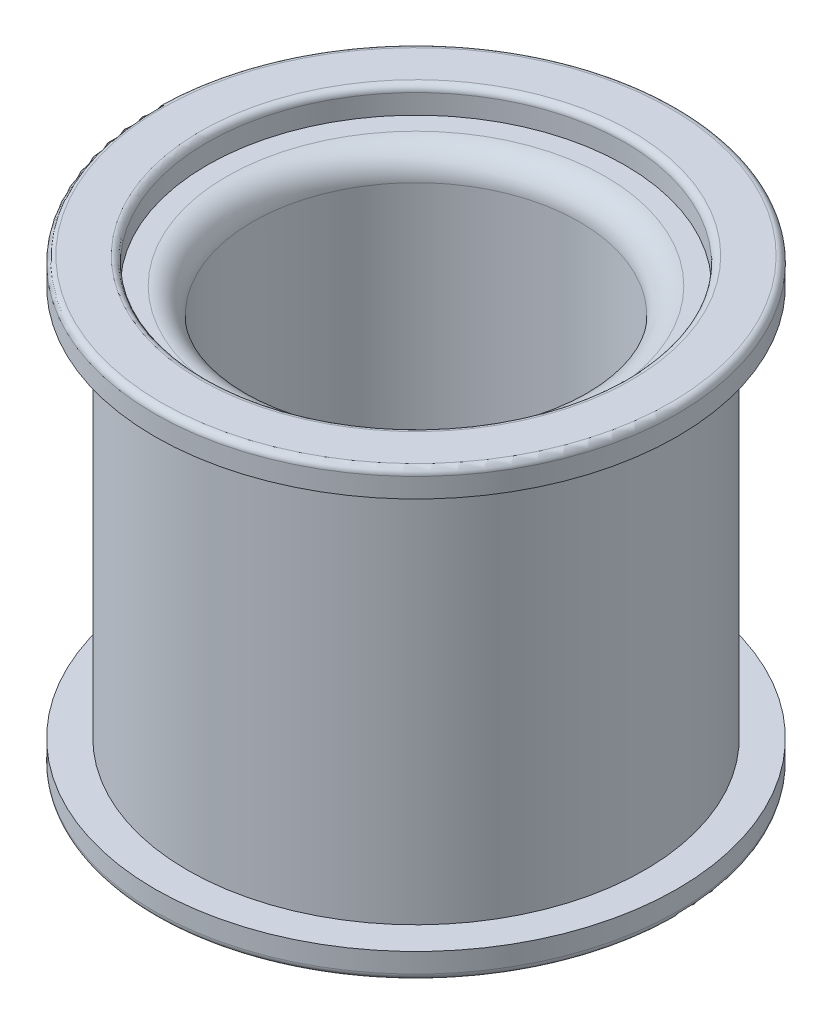
SolidWorks part; units mm, degrees
material "Guma"
ref_plane "Płaszczyzna przednia" through (0, 0, 0) normal (0, 0, 1) x (1, 0, 0)
ref_plane "Płaszczyzna górna" through (0, 0, 0) normal (0, 1, 0) x (1, 0, 0)
ref_plane "Płaszczyzna prawa" through (0, 0, 0) normal (1, 0, 0) x (0, 0, -1)
sketch "Szkic1" plane through (0, 0, 0) normal (0, 1, 0) x (1, 0, 0)
  circle A0 centre (0, 0) radius 17.5
  circle A1 centre (0, 0) radius 12.5
  dimension "D1" = 25
  dimension "D2" = 35
extrude "Dodanie-wyciągnięcie1" add sketch "Szkic1" along normal blind 15
sketch "Szkic2" plane through (0, 15, 0) normal (0, 1, 0) x (1, 0, 0)
  circle A0 centre (0, 0) radius 20
  circle A1 centre (0, 0) radius 16
  dimension "D1" = 40
  dimension "D2" = 32
extrude "Dodanie-wyciągnięcie2" add sketch "Szkic2" along normal blind 2 separate body
fillet "Zaokrąglenie1" radius 0.5 2 edges at (0, 17, 16) (0, 17, 20)
fillet "Zaokrąglenie2" radius 2 1 edges at (0, 15, 12.5)
mirror "Lustro3" about plane through (0, 0, 0) normal (0, 1, 0) of "Zaokrąglenie2", "Dodanie-wyciągnięcie1"
sketch "Szkic3" plane through (0, -15, 0) normal (0, -1, 0) x (1, 0, 0)
  circle A0 centre (0, 0) radius 20
  circle A1 centre (0, 0) radius 16
  dimension "D1" = 40
  dimension "D2" = 32
extrude "Dodanie-wyciągnięcie3" add sketch "Szkic3" along normal blind 2 separate body
fillet "Zaokrąglenie3" radius 0.5 2 edges at (0, -17, -20) (0, -17, -16)
